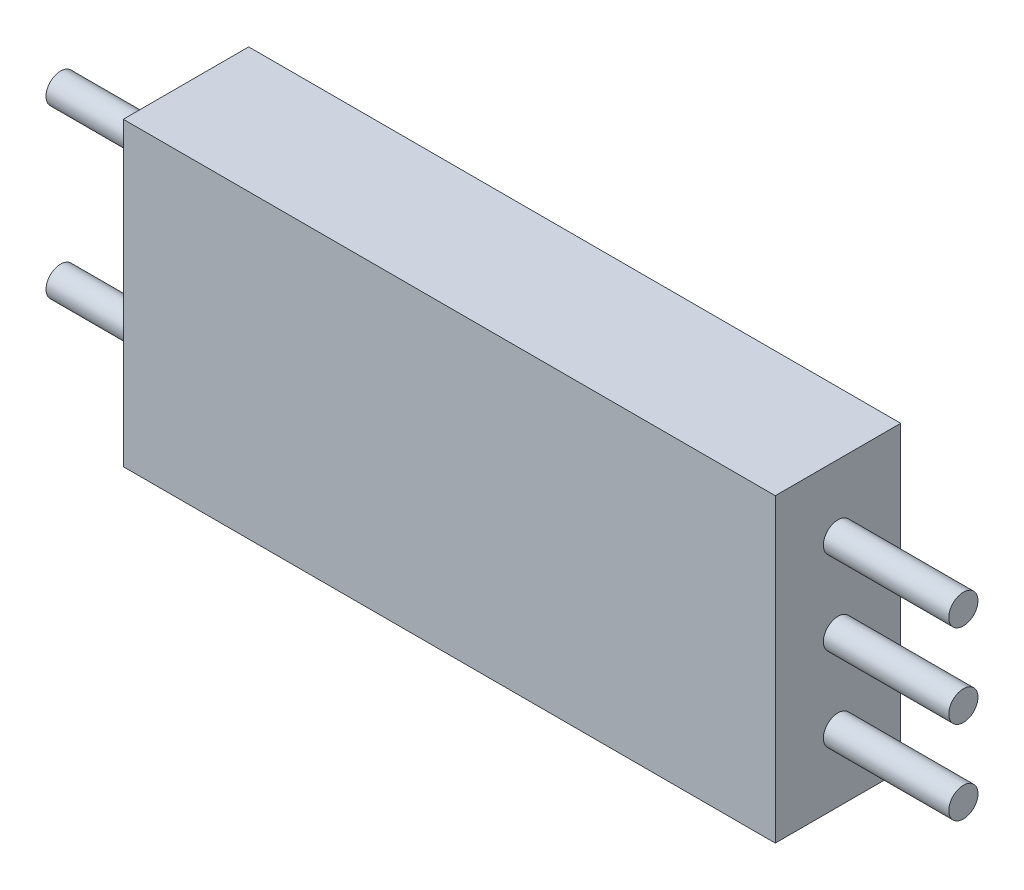
SolidWorks part; units mm, degrees
ref_plane "Front Plane" through (0, 0, 0) normal (0, 0, 1) x (1, 0, 0)
ref_plane "Top Plane" through (0, 0, 0) normal (0, 1, 0) x (1, 0, 0)
ref_plane "Right Plane" through (0, 0, 0) normal (1, 0, 0) x (0, 0, -1)
sketch "Эскиз2" plane through (0, 0, 0) normal (0, 0, 1) x (1, 0, 0)
  line L1 (-39, -18) -> (39, -18)
  line L2 (-39, -18) -> (-39, 18)
  line L3 (-39, 18) -> (39, 18)
  line L4 (39, -18) -> (39, 18)
  line L5 (-39, -18) -> (39, 18) construction
  line L6 (-39, 18) -> (39, -18) construction
  point P0 (0, 0)
  dimension "D1" = 78
  dimension "D2" = 36
extrude "Бобышка-Вытянуть1" add sketch "Эскиз2" along normal mid plane 15
sketch "Эскиз3" plane through (39, 0, 0) normal (1, 0, 0) x (0, 0, -1)
  line L0 (0, -18) -> (0, 18) construction
  line L1 (-7.5, -18) -> (7.5, -18) construction
  line L2 (-7.5, 18) -> (7.5, 18) construction
  circle A0 centre (0, -10) radius 1.75
  circle A1 centre (0, 0) radius 1.75
  circle A2 centre (0, 10) radius 1.75
  dimension "D1" = 3.5
  dimension "D2" = 10
  dimension "D3" = 10
extrude "Бобышка-Вытянуть2" add sketch "Эскиз3" along normal blind 15
sketch "Эскиз4" plane through (-39, 0, 0) normal (-1, 0, 0) x (0, 0, 1)
  line L0 (0, 18) -> (0, -18) construction
  line L1 (7.5, 18) -> (-7.5, 18) construction
  line L2 (7.5, -18) -> (-7.5, -18) construction
  circle A0 centre (0, 10) radius 1.75
  circle A1 centre (0, -10) radius 1.75
  point P7 (0, 18)
  point P10 (0, -18)
  dimension "D1" = 3.5
  dimension "D2" = 20
  dimension "D3" = 36
  dimension "D4" = 8
extrude "Бобышка-Вытянуть3" add sketch "Эскиз4" along normal blind 15
